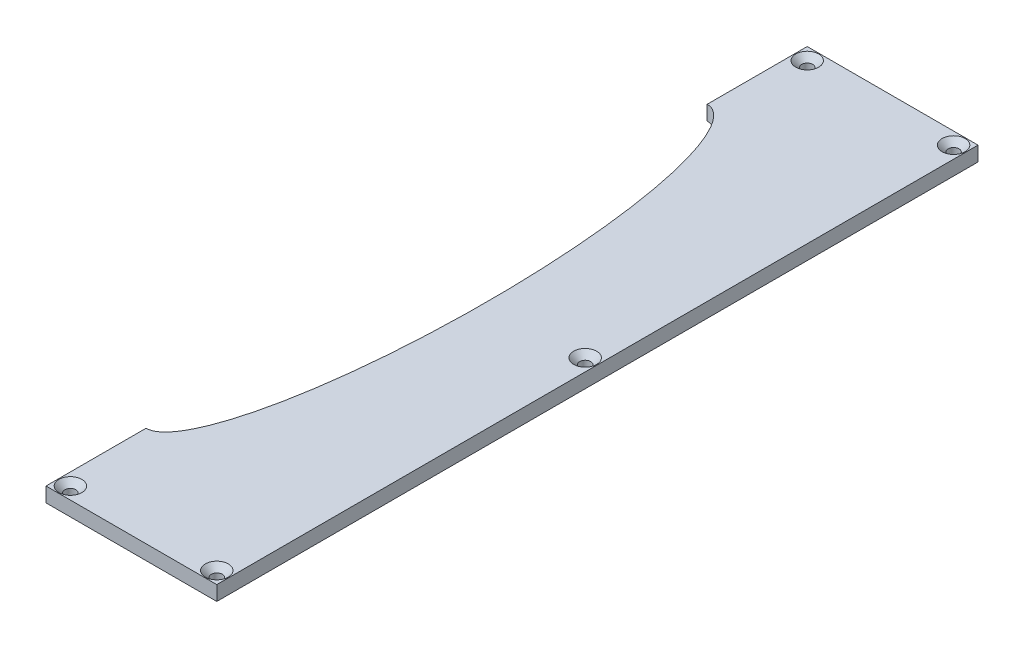
SolidWorks part; units mm, degrees
ref_plane "Front Plane" through (0, 0, 0) normal (0, 0, 1) x (1, 0, 0)
ref_plane "Top Plane" through (0, 0, 0) normal (0, 1, 0) x (1, 0, 0)
ref_plane "Right Plane" through (0, 0, 0) normal (1, 0, 0) x (0, 0, -1)
sketch "Sketch1" plane through (0, 0, 0) normal (0, 1, 0) x (1, 0, 0)
  line L0 (0, 115) -> (0, 156)
  line L1 (0, 156) -> (70, 156)
  line L2 (70, 156) -> (70, -156)
  line L3 (70, -156) -> (0, -156)
  line L4 (0, -156) -> (0, -115)
  ellipse E0 centre (0, 0) end of major axis (0, 115) minor radius 25
  dimension "D1" = 230
  dimension "D2" = 50
  dimension "D3" = 156
  dimension "D4" = 312
  dimension "D5" = 70
extrude "Boss-Extrude1" add sketch "Sketch1" along normal blind 6 contours E0 L4 L3 L2 L1 L0
sketch "Sketch2" plane through (0, 6, 0) normal (0, 1, 0) x (1, 0, 0)
  line L0 (70, -156) -> (0, -156) construction
  line L1 (70, 156) -> (70, -156) construction
  line L2 (0, 115) -> (0, 156) construction
  line L3 (0, 156) -> (70, 156) construction
  point P0 (5, 151)
  point P1 (65, -151)
  point P8 (65, 151)
  point P9 (5, -151)
  point P10 (65, 0)
  dimension "D1" = 5
  dimension "D2" = 5
  dimension "D3" = 5
  dimension "D4" = 5
hole_wizard "CSK for M4 Countersunk Flat Head Screw1" positions "Sketch3" profile "Sketch4" countersink size "M4" standard "ISO"
sketch "Sketch3" plane through (0, 6, 0) normal (0, 1, 0) x (1, 0, 0)
  point P0 (5, 151)
  point P3 (65, 151)
  point P6 (65, 0)
  point P9 (65, -151)
  point P12 (5, -151)
sketch "Sketch4" plane through (5, 6, -151) normal (1, 0, 0) x (0, 0, 1)
  line L0 (0, 0) -> (0, 11.3519)
  line L1 (0, 11.3519) -> (2.25, 10)
  line L2 (2.25, 10) -> (2.25, 2.45)
  line L3 (2.25, 2.45) -> (4.7, 0)
  line L5 (4.7, 0) -> (0, 0)
  line L6 (-2.25, 2.45) -> (-4.7, 0) construction
  line L10 (0, 11.3519) -> (-2.25, 10) construction
  line L11 (0, -6.35) -> (0, 107.95) construction
  dimension "Hole Dia." = 4.5
  dimension "Hole Depth" = 10
  dimension "Near C'Sink Dia." = 9.4
  dimension "Near C'Sink Angle" = 90
  dimension "Drill Angle" = 118
